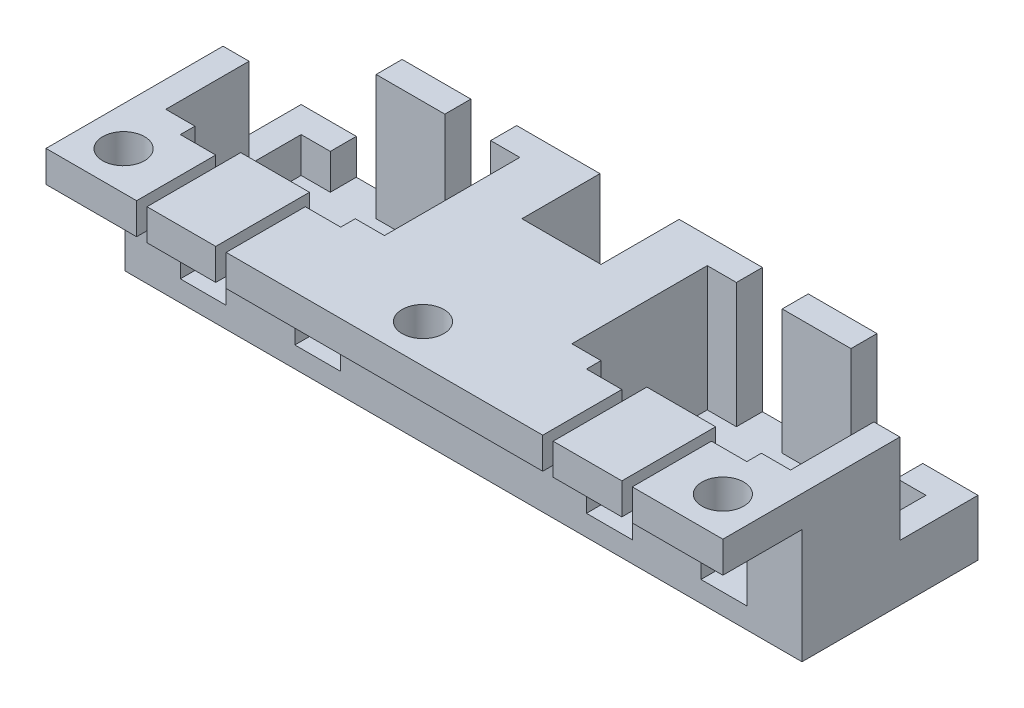
SolidWorks part; units mm, degrees
material "Delrin 2700 NC010, Low Viscosity Acetal Copolymer (SS)"
ref_plane "Front Plane" through (0, 0, 0) normal (0, 0, 1) x (1, 0, 0)
ref_plane "Top Plane" through (0, 0, 0) normal (0, 1, 0) x (1, 0, 0)
ref_plane "Right Plane" through (0, 0, 0) normal (1, 0, 0) x (0, 0, -1)
sketch "Sketch1" plane through (0, 0, 0) normal (0, 1, 0) x (1, 0, 0)
  line L0 (41.275, 5.588) -> (-41.275, 5.588)
  line L1 (-41.275, -15.875) -> (41.275, -15.875)
  line L2 (-41.275, -15.875) -> (-41.275, 5.588)
  line L4 (41.275, -15.875) -> (41.275, 5.588)
  line L5 (-41.275, -15.875) -> (41.275, 15.875) construction
  line L6 (-41.275, 15.875) -> (41.275, -15.875) construction
  point P0 (0, 0)
  dimension "D1" = 82.55
  dimension "D2" = 21.463
extrude "Plate" add sketch "Sketch1" along normal mid plane 2.54
sketch "Sketch4" plane through (0, 0, 15.875) normal (0, 0, 1) x (1, 0, 0)
  line L1 (-41.275, 1.27) -> (41.275, 1.27)
  line L2 (-41.275, 1.27) -> (-41.275, 16.51)
  line L3 (-41.275, 16.51) -> (41.275, 16.51)
  line L4 (41.275, 1.27) -> (41.275, 16.51)
  line L5 (41.275, 1.27) -> (41.275, -1.27) construction
  dimension "D1" = 15.24
  dimension "D2" = 0
extrude "Boss-Extrude1" add sketch "Sketch4" against normal blind 1.778
sketch "Sketch5" plane through (0, 0, 14.097) normal (0, 0, -1) x (-1, 0, 0)
  line L0 (41.275, 1.27) -> (-41.275, 1.27) construction
  line L1 (-41.275, 16.51) -> (-38.1, 16.51)
  line L2 (-41.275, 16.51) -> (-41.275, 1.27)
  line L3 (-41.275, 1.27) -> (-38.1, 1.27)
  line L4 (-38.1, 16.51) -> (-38.1, 1.27)
  line L6 (41.275, 16.51) -> (38.1, 16.51)
  line L7 (41.275, 16.51) -> (41.275, 1.27)
  line L8 (41.275, 1.27) -> (38.1, 1.27)
  line L9 (38.1, 16.51) -> (38.1, 1.27)
  dimension "D1" = 3.175
  dimension "D2" = 3.175
extrude "Boss-Extrude2" add sketch "Sketch5" along normal blind 19.685
sketch "Sketch9" plane through (38.1, 0, 0) normal (-1, 0, 0) x (0, 0, 1)
  line L0 (-5.588, 16.51) -> (14.097, 16.51) construction
  line L1 (-2.413, 16.51) -> (-5.588, 16.51)
  line L2 (-2.413, 16.51) -> (-2.413, 1.27)
  line L3 (-2.413, 1.27) -> (-5.588, 1.27)
  line L4 (-5.588, 16.51) -> (-5.588, 1.27)
  line L5 (-5.588, 1.27) -> (14.097, 1.27) construction
  line L6 (14.097, 1.27) -> (14.097, 16.51) construction
  dimension "D1" = 16.51
  dimension "D2" = 3.175
extrude "Boss-Extrude5" add sketch "Sketch9" along normal up to next
sketch "Sketch10" plane through (0, 0, 14.097) normal (0, 0, -1) x (-1, 0, 0)
  line L0 (38.1, 1.27) -> (-38.1, 1.27) construction
  line L1 (-8.255, 1.27) -> (-11.43, 1.27)
  line L2 (-8.255, 16.51) -> (8.255, 16.51)
  line L3 (-8.255, 16.51) -> (-11.43, 16.51)
  line L4 (-11.43, 16.51) -> (-11.43, 1.27)
  line L5 (-38.1, 16.51) -> (38.1, 16.51) construction
  line L6 (-8.255, 1.27) -> (8.255, 1.27)
  line L7 (0, 1.27) -> (0, 16.51) construction
  line L8 (11.43, 1.27) -> (11.43, 16.51)
  line L9 (8.255, 16.51) -> (11.43, 16.51)
  line L10 (-38.1, 1.27) -> (-38.1, 16.51) construction
  line L11 (8.255, 1.27) -> (11.43, 1.27)
  dimension "D1" = 26.67
  dimension "D2" = 3.175
extrude "Boss-Extrude6" add sketch "Sketch10" along normal up to next
sketch "Sketch11" plane through (0, 0, -5.588) normal (0, 0, -1) x (-1, 0, 0)
  line L0 (41.275, 16.51) -> (-41.275, 16.51) construction
  line L1 (-34.544, 16.51) -> (-28.956, 16.51)
  line L2 (-34.544, 16.51) -> (-34.544, 1.27)
  line L3 (-34.544, 1.27) -> (-28.956, 1.27)
  line L4 (-28.956, 16.51) -> (-28.956, 1.27)
  line L5 (38.1, 1.27) -> (-38.1, 1.27) construction
  line L7 (0, 1.27) -> (0, 16.51) construction
  line L8 (28.956, 16.51) -> (28.956, 1.27)
  line L9 (34.544, 1.27) -> (28.956, 1.27)
  line L10 (34.544, 16.51) -> (34.544, 1.27)
  line L11 (34.544, 16.51) -> (28.956, 16.51)
  line L12 (-41.275, 16.51) -> (-41.275, -1.27) construction
  line L13 (41.275, 16.51) -> (-41.275, 16.51) construction
  line L14 (-20.574, 16.51) -> (-14.986, 16.51)
  line L15 (-20.574, 16.51) -> (-20.574, 1.27)
  line L16 (-20.574, 1.27) -> (-14.986, 1.27)
  line L17 (-14.986, 16.51) -> (-14.986, 1.27)
  line L18 (14.986, 16.51) -> (14.986, 1.27)
  line L19 (20.574, 1.27) -> (14.986, 1.27)
  line L20 (20.574, 16.51) -> (20.574, 1.27)
  line L21 (20.574, 16.51) -> (14.986, 16.51)
  dimension "D1" = 6.731
  dimension "D2" = 5.588
  dimension "D3" = 15.24
  dimension "D4" = 20.701
  dimension "D5" = 5.588
extrude "Cut-Extrude1" cut sketch "Sketch11" against normal through all
sketch "Sketch13" plane through (0, 0, 15.875) normal (0, 0, 1) x (1, 0, 0)
  line L0 (41.275, 16.51) -> (41.275, -1.27) construction
  line L1 (-41.275, 16.51) -> (41.275, 16.51)
  line L2 (-41.275, 16.51) -> (-41.275, 12.7)
  line L3 (-41.275, 12.7) -> (41.275, 12.7)
  line L4 (41.275, 16.51) -> (41.275, 12.7)
  dimension "D1" = 3.81
extrude "Boss-Extrude7" add sketch "Sketch13" along normal blind 9.652
hole_wizard "#10 Clearance Hole1" positions "3DSketch1" profile "Sketch14" hole size "#10" standard "ANSI Inch" end condition through all
sketch3d "3DSketch1"
  line L0 (41.275, 16.51, -5.588) -> (41.275, 16.51, 25.527) construction
  line L1 (41.275, 16.51, 25.527) -> (-41.275, 16.51, 25.527) construction
  line L2 (-41.275, 16.51, -5.588) -> (-41.275, 16.51, 25.527) construction
  point P0 (36.5125, 16.51, 20.7645)
  point P2 (0, 16.51, 20.828)
  point P4 (-36.5125, 16.51, 20.828)
  dimension "D1" = 4.7625
  dimension "D2" = 4.7625
  dimension "D3" = 41.275
  dimension "D4" = 4.7625
  dimension "D5" = 4.699
  dimension "D6" = 4.699
sketch "Sketch14" plane through (36.5125, 16.51, 20.7645) normal (1, 0, 0) x (0, 0, 1)
  line L0 (0, 0) -> (0, 17.78)
  line L1 (0, 17.78) -> (2.5527, 17.78)
  line L2 (2.5527, 17.78) -> (2.5527, 0)
  line L5 (2.5527, 0) -> (0, 0)
  line L11 (0, -6.35) -> (0, 107.95) construction
  dimension "Thru Hole Dia." = 5.1054
  dimension "Thru Hole Depth" = 17.78
sketch "Sketch16" plane through (0, 0, -5.588) normal (0, 0, -1) x (-1, 0, 0)
  line L0 (0, 16.51) -> (0, -1.27) construction
  line L1 (-41.275, 16.51) -> (-34.29, 16.51)
  line L2 (-41.275, 16.51) -> (-41.275, 5.588)
  line L3 (-41.275, 5.588) -> (-34.29, 5.588)
  line L4 (-34.29, 16.51) -> (-34.29, 5.588)
  line L5 (28.956, 16.51) -> (20.574, 16.51) construction
  line L6 (-41.275, -1.27) -> (41.275, -1.27) construction
  line L7 (34.29, 16.51) -> (34.29, 5.588)
  line L8 (41.275, 5.588) -> (34.29, 5.588)
  line L9 (41.275, 16.51) -> (41.275, 5.588)
  line L10 (41.275, 16.51) -> (34.29, 16.51)
  line L12 (-4.826, 16.51) -> (4.826, 16.51)
  line L13 (-4.826, 16.51) -> (-4.826, 5.588)
  line L14 (-4.826, 5.588) -> (4.826, 5.588)
  line L15 (4.826, 16.51) -> (4.826, 5.588)
  point P19 (-61.8958, 13.9691)
  point P20 (-47.7542, 34.5553)
  dimension "D1" = 10.922
  dimension "D2" = 6.985
  dimension "D3" = 9.652
  dimension "D4" = 10.922
  dimension "D5" = 4.826
extrude "Cut-Extrude4" cut sketch "Sketch16" against normal blind 9.525
sketch "Sketch18" plane through (0, 16.51, 0) normal (0, 1, 0) x (1, 0, 0)
  line L0 (41.275, -25.527) -> (-41.275, -25.527) construction
  line L1 (-28.956, -15.875) -> (-30.226, -15.875)
  line L2 (-28.956, -15.875) -> (-28.956, -25.527)
  line L3 (-28.956, -25.527) -> (-30.226, -25.527)
  line L4 (-30.226, -15.875) -> (-30.226, -25.527)
  line L6 (-20.574, -15.875) -> (-19.304, -15.875)
  line L7 (-20.574, -15.875) -> (-20.574, -25.527)
  line L8 (-20.574, -25.527) -> (-19.304, -25.527)
  line L9 (-19.304, -15.875) -> (-19.304, -25.527)
  line L11 (0, -25.527) -> (0, 1.5768) construction
  line L12 (19.304, -15.875) -> (19.304, -25.527)
  line L13 (20.574, -25.527) -> (19.304, -25.527)
  line L14 (20.574, -15.875) -> (20.574, -25.527)
  line L15 (20.574, -15.875) -> (19.304, -15.875)
  line L16 (30.226, -15.875) -> (30.226, -25.527)
  line L17 (28.956, -25.527) -> (30.226, -25.527)
  line L18 (28.956, -15.875) -> (28.956, -25.527)
  line L19 (28.956, -15.875) -> (30.226, -15.875)
  dimension "D1" = 1.27
  dimension "D2" = 1.27
extrude "Cut-Extrude6" cut sketch "Sketch18" against normal through all
